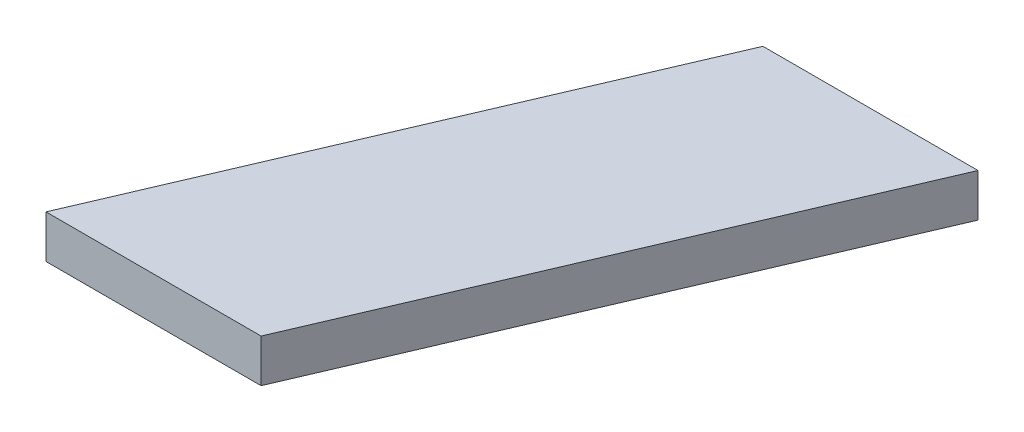
SolidWorks part; units mm, degrees
ref_plane "Front Plane" through (0, 0, 0) normal (0, 0, 1) x (1, 0, 0)
ref_plane "Top Plane" through (0, 0, 0) normal (0, 1, 0) x (1, 0, 0)
ref_plane "Right Plane" through (0, 0, 0) normal (1, 0, 0) x (0, 0, -1)
sketch "Sketch1" plane through (0, 0, 0) normal (0, 1, 0) x (1, 0, 0)
  line L1 (1.5, 3.5) -> (0, 3.5)
  line L6 (0, 3.5) -> (-1.5, 0)
  line L7 (-1.5, 0) -> (0, 0)
  line L8 (1.5, 3.5) -> (0, 0)
  dimension "D1" = 1.5
  dimension "D2" = 3.5
  dimension "D3" = 1.5
extrude "Boss-Extrude1" add sketch "Sketch1" along normal blind 0.3
equation "\"t\"= 0.3'thickness of the sheets"
equation "\"FlexJoint\"= 0.15'Width of flextures"
equation "\"FoldJoint\"= 0.4'Width of folding joints"
equation "\"AssembleAngle\"= 90'Angle of assembly parts"
equation "\"D1@Boss-Extrude1\"=\"t\""
